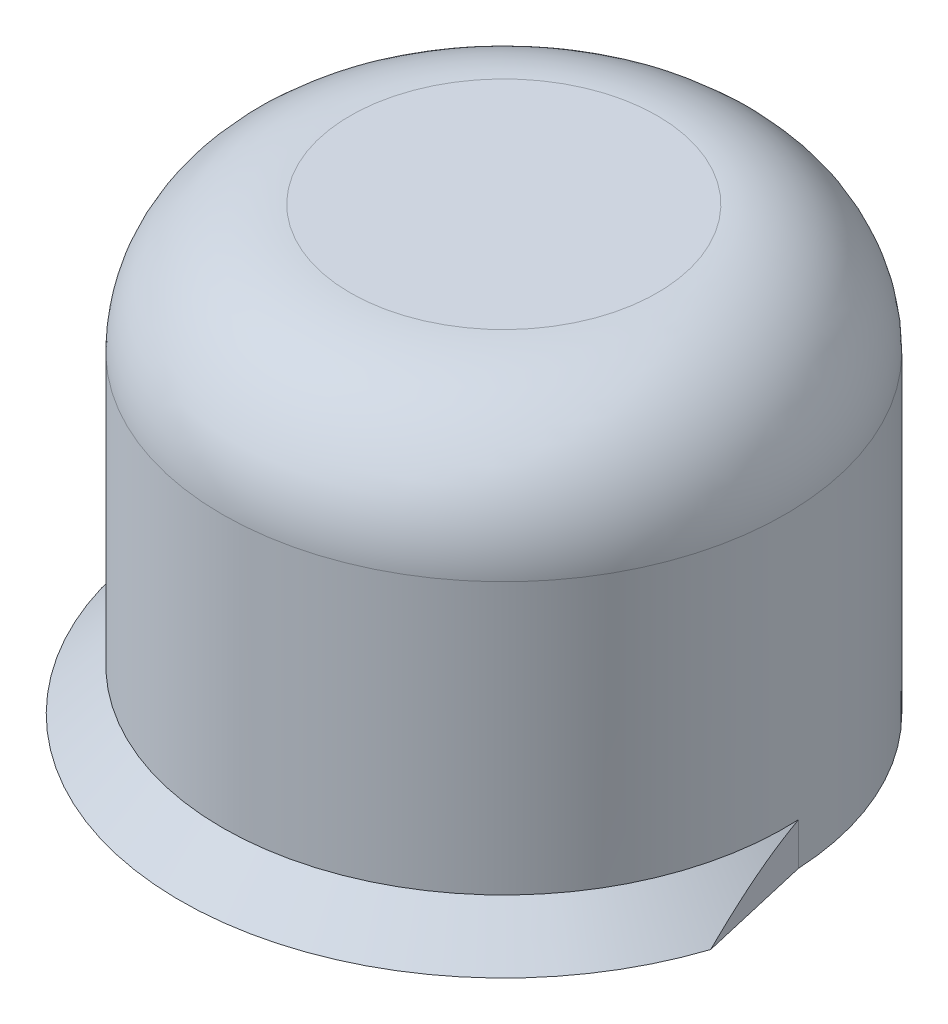
SolidWorks part; units mm, degrees
ref_plane "Front" through (0, 0, 0) normal (0, 0, 1) x (1, 0, 0)
ref_plane "Top" through (0, 0, 0) normal (0, 1, 0) x (1, 0, 0)
ref_plane "Right" through (0, 0, 0) normal (1, 0, 0) x (0, 0, -1)
sketch "Sketch1" plane through (0, 0, 0) normal (1, 0, 0) x (0, 0, -1)
  line L3 (0, 5.9) -> (1.3797, 5.9)
  line L4 (1.5796, 5.7048) -> (1.7155, 0)
  line L5 (1.7155, 0) -> (5.3, 0)
  line L6 (5.3, 0) -> (4.5, 0.8)
  line L7 (4.5, 0.8) -> (4.5, 2.6)
  line L8 (0, 7.1) -> (0, 5.9)
  line L9 (1.5796, 5.7048) -> (1.725, -0.4) construction
  line L10 (4.5, 0.8) -> (5.7, -0.4) construction
  line L11 (1.3797, 5.9) -> (-1.3797, 5.9) construction
  line L12 (0, 7.1) -> (0, -1.3236) construction
  line L13 (5.3, 0) -> (0, 0) construction
  arc A0 (1.3797, 5.9) -> (1.5796, 5.7048) centre (1.3797, 5.7) cw
  arc A1 (4.5, 2.6) -> (0, 7.1) centre (0, 2.6) ccw
  point P19 (1.575, 5.9)
  dimension "D5" = 4.5
  dimension "D10" = 0.2
  dimension "D1" = 0.4
  dimension "D2" = 1.3236
  dimension "D3" = 5.9
  dimension "D4" = 1.2
  dimension "D6" = 45
  dimension "D7" = 5.3
  dimension "D8" = 1.7155
  dimension "D9" = 1.575
sketch "Sketch2" plane through (0, 0, 0) normal (1, 0, 0) x (0, 0, -1)
  line L6 (2.4, 7) -> (0, 7)
  line L7 (0, 7.1) -> (0, 5.9) construction
  line L8 (0, 7) -> (0, 6)
  line L9 (0, 6) -> (0.1, 6)
  line L10 (0, 7) -> (0, 0) construction
  line L12 (4.4, 0.7586) -> (4.4, 2.6)
  line L13 (5.0586, 0.1) -> (4.4, 0.7586)
  line L14 (1.8131, 0.1) -> (5.0586, 0.1)
  line L15 (1.6796, 5.7071) -> (1.8131, 0.1)
  line L16 (0.1, 6) -> (1.3797, 6)
  line L17 (0.1, 6.9989) -> (0.1, 6)
  line L18 (4.4, 0.7586) -> (4.4, 5)
  line L19 (5.0586, 0.1) -> (4.4, 0.7586)
  line L20 (1.8131, 0.1) -> (5.0586, 0.1)
  line L21 (1.6796, 5.7071) -> (1.8131, 0.1)
  line L22 (0.1, 6) -> (1.3797, 6)
  arc A0 (4.4, 5) -> (2.4, 7) centre (2.4, 5) ccw
  arc A4 (1.6796, 5.7071) -> (1.3797, 6) centre (1.3797, 5.7) ccw
  arc A5 (4.4, 2.6) -> (0.1, 6.9989) centre (0, 2.6) ccw
  arc A6 (1.6796, 5.7071) -> (1.3797, 6) centre (1.3797, 5.7) ccw
  dimension "D3" = 2
  dimension "D2" = 1
  dimension "D1" = 0.1
revolve "Revolve1" add sketch "Sketch2" angle 360 about L10
sketch "Sketch39" plane through (0, 0.1, 0) normal (0, -1, 0) x (1, 0, 0)
  line L0 (0, 0) -> (2.4223, -7.4159) construction
  line L1 (4.8662, 1.3819) -> (4.4943, -0.2272) construction
  line L2 (0, -5.0586) -> (0, 0) construction
  line L3 (0, 0) -> (4.8662, 1.3819) construction
  line L4 (4.8502, 1.7569) -> (4.3948, -0.2134)
  arc A0 (0.8317, -4.3207) -> (4.3948, -0.2134) centre (0, 0) ccw
  arc A1 (0.8649, -4.4161) -> (0, -5.0586) centre (2.4223, -7.4159) ccw construction
  arc A2 (0.8317, -4.3207) -> (-0.2222, -5.1538) centre (2.4223, -7.4159) ccw
  arc A3 (0.8649, -4.4161) -> (4.4943, -0.2272) centre (0, 0) ccw construction
  arc A4 (-0.2222, -5.1538) -> (4.8502, 1.7569) centre (0, 0) ccw
  arc A5 (0, -5.0586) -> (4.8662, 1.3819) centre (0, 0) ccw construction
  dimension "D1" = 5.0586
  dimension "D2" = 4.5
  dimension "D3" = 3.38
  dimension "D4" = 105.854
  dimension "D5" = 61.133
  dimension "D6" = 18.088
  dimension "D7" = 0.1
extrude "Cut-Extrude1" cut sketch "Sketch39" against normal up to next
